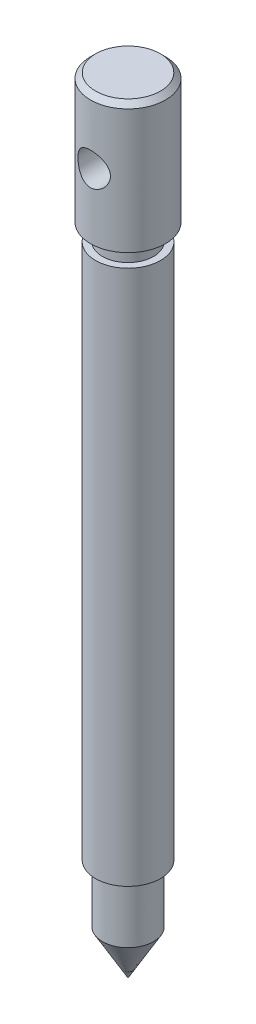
SolidWorks part; units mm, degrees
ref_plane "Alzado" through (0, 0, 0) normal (0, 0, 1) x (1, 0, 0)
ref_plane "Planta" through (0, 0, 0) normal (0, 1, 0) x (1, 0, 0)
ref_plane "Vista lateral" through (0, 0, 0) normal (1, 0, 0) x (0, 0, -1)
sketch "Croquis1" plane through (0, 0, 0) normal (0, 0, 1) x (1, 0, 0)
  line L0 (0, 0) -> (0, 230) construction
  line L1 (0, 0) -> (7.5, 12.9904)
  line L2 (7.5, 12.9904) -> (7.5, 30)
  line L3 (7.5, 30) -> (9.525, 30)
  line L4 (9.525, 30) -> (9.525, 187)
  line L5 (9.525, 187) -> (7.5, 187)
  line L6 (7.5, 187) -> (7.5, 192)
  line L7 (7.5, 192) -> (11, 192)
  line L8 (11, 192) -> (11, 230)
  line L9 (11, 230) -> (0, 230)
  line L10 (0, 0) -> (0, 230)
  point P3 (7.5, 189.5)
  point P12 (7.5, 21.4952)
  dimension "D1" = 230
  dimension "D2" = 30
  dimension "D3" = 15
  dimension "D4" = 30
  dimension "D5" = 157
  dimension "D6" = 19.05
  dimension "D7" = 22
  dimension "D8" = 5
revolve "Revolución1" add sketch "Croquis1" angle 360 about L0
cosmetic thread "Rosca cosmética1" parameters "D2"=16.0249
sketch "Croquis2" plane through (0, 0, 0) normal (0, 0, 1) x (1, 0, 0)
  line L0 (11, 230) -> (-11, 230) construction
  circle A0 centre (0, 211) radius 4.7625
  dimension "D2" = 9.525
  dimension "D1" = 19
extrude "Cortar-Extruir1" cut sketch "Croquis2" against normal through all both and the other way through all
chamfer "Chaflán1" distance 1.5 angle 45 1 edges at (0, 230, -11)
